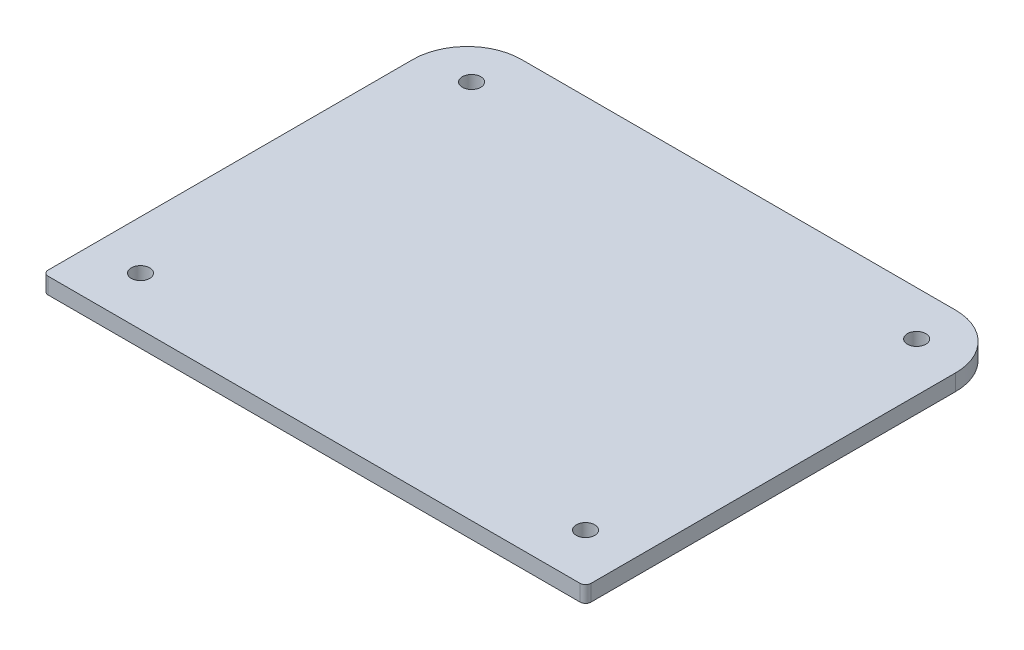
SolidWorks part; units mm, degrees
ref_plane "Front Plane" through (0, 0, 0) normal (0, 0, 1) x (1, 0, 0)
ref_plane "Top Plane" through (0, 0, 0) normal (0, 1, 0) x (1, 0, 0)
ref_plane "Right Plane" through (0, 0, 0) normal (1, 0, 0) x (0, 0, -1)
sketch "Sketch1" plane through (0, 33, 0) normal (0, 1, 0) x (1, 0, 0)
  line L1 (-50, 50) -> (50, 50)
  line L2 (-50, 50) -> (-50, -50)
  line L3 (-50, -50) -> (50, -50)
  line L4 (50, 50) -> (50, -50)
  line L5 (-50, 50) -> (50, -50) construction
  line L6 (-50, -50) -> (50, 50) construction
  point P0 (0, 0)
  dimension "D1" = 100
  dimension "D2" = 100
extrude "Boss-Extrude1" add sketch "Sketch1" along normal blind 3
sketch "Sketch2" plane through (0, 36, 0) normal (0, 1, 0) x (1, 0, 0)
  line L0 (-50, 50) -> (-41, 20) construction
  line L1 (-49.1879, -50) -> (-41, -41) construction
  line L2 (-50, -50) -> (50, -50) construction
  line L3 (50, -50) -> (41, -41) construction
  line L4 (50, 50) -> (-50, 50) construction
  line L5 (50, -50) -> (50, 50) construction
  line L6 (50, 50) -> (41, 20) construction
  line L7 (-50, 50) -> (-50, -50) construction
  circle A0 centre (-41, 20) radius 1.7
  circle A1 centre (41, 20) radius 1.7
  circle A2 centre (41, -41) radius 1.7
  circle A3 centre (-41, -41) radius 1.7
  dimension "D9" = 3.4
  dimension "D10" = 3.4
  dimension "D11" = 3.4
  dimension "D12" = 3.4
  dimension "D1" = 30
  dimension "D2" = 9
  dimension "D3" = 30
  dimension "D4" = 9
  dimension "D5" = 9
  dimension "D6" = 9
  dimension "D7" = 9
  dimension "D8" = 9
extrude "Cut-Extrude1" cut sketch "Sketch2" against normal up to surface (3 mm away) up to face at (0, 33, 0)
sketch "Sketch6" plane through (0, 36, 0) normal (0, 1, 0) x (1, 0, 0)
  line L0 (50, -50) -> (50, 50) construction
  line L1 (-50, 50) -> (50, 50)
  line L2 (-50, 50) -> (-50, 28.1911)
  line L3 (-50, 28.1911) -> (50, 28.1911)
  line L4 (50, 50) -> (50, 28.1911)
extrude "Cut-Extrude2" cut sketch "Sketch6" against normal up to surface (3 mm away) up to face at (-41, 33, 42.7)
fillet "Fillet2" radius 10 2 edges at (50, 34.5, -28.1911) (-50, 34.5, -28.1911)
fillet "Fillet3" radius 1 2 edges at (-50, 34.5, 50) (50, 34.5, 50)
